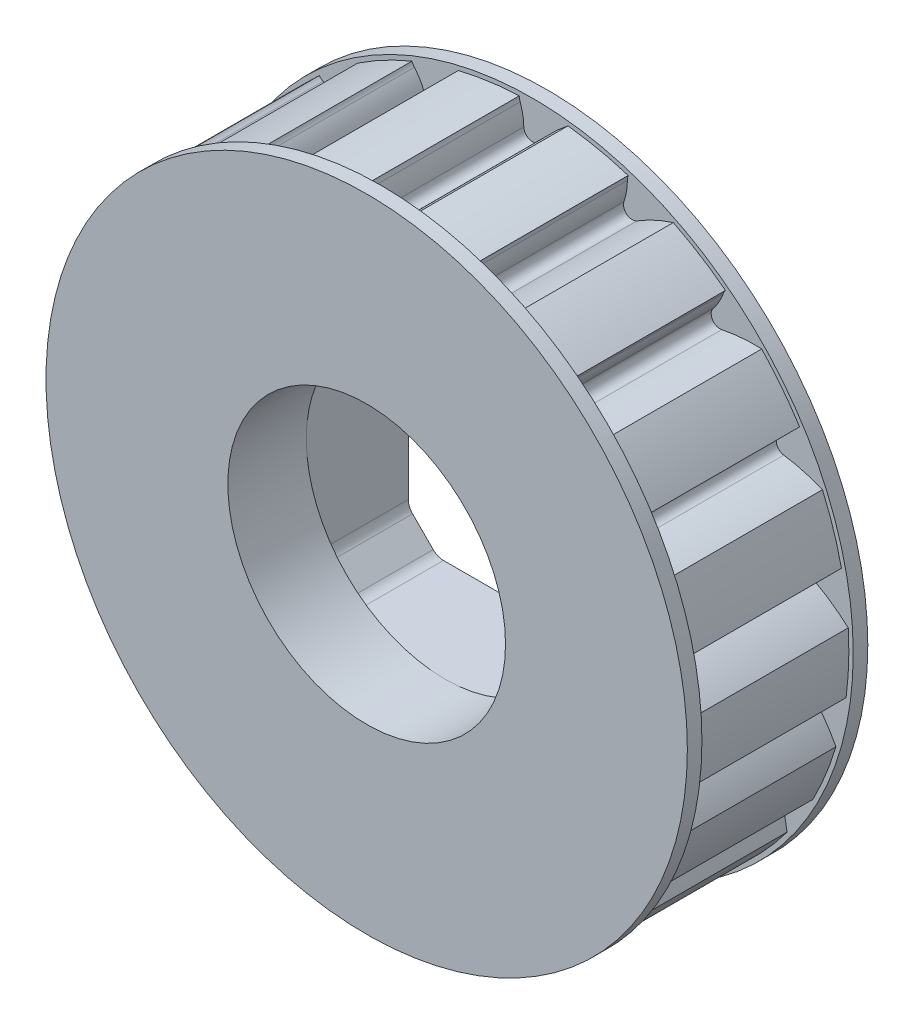
SolidWorks part; units mm, degrees
material "PA Type 6"
ref_plane "Front Plane" through (0, 0, 0) normal (0, 0, 1) x (1, 0, 0)
ref_plane "Top Plane" through (0, 0, 0) normal (0, 1, 0) x (1, 0, 0)
ref_plane "Right Plane" through (0, 0, 0) normal (1, 0, 0) x (0, 0, -1)
sketch "Sketch1" plane through (0, 0, 0) normal (0, 0, 1) x (1, 0, 0)
  line L9 (9.525, -7.1108) -> (9.525, 7.1108)
  line L10 (7.8179, -9.2321) -> (9.2321, -7.8179)
  line L11 (-7.1108, -9.525) -> (7.1108, -9.525)
  line L12 (-9.2321, -7.8179) -> (-7.8179, -9.2321)
  line L13 (-9.525, 7.1108) -> (-9.525, -7.1108)
  line L14 (-7.8179, 9.2321) -> (-9.2321, 7.8179)
  line L15 (7.1108, 9.525) -> (-7.1108, 9.525)
  line L16 (9.2321, 7.8179) -> (7.8179, 9.2321)
  line L17 (9.525, -7.1108) -> (9.525, 7.1108)
  line L18 (7.8179, -9.2321) -> (9.2321, -7.8179)
  line L19 (-7.1108, -9.525) -> (7.1108, -9.525)
  line L20 (-9.2321, -7.8179) -> (-7.8179, -9.2321)
  line L21 (-9.525, 7.1108) -> (-9.525, -7.1108)
  line L22 (-7.8179, 9.2321) -> (-9.2321, 7.8179)
  line L23 (7.1108, 9.525) -> (-7.1108, 9.525)
  line L24 (9.2321, 7.8179) -> (7.8179, 9.2321)
  circle A0 centre (0, 0) radius 25
  circle A1 centre (0, 0) radius 9.525 construction
  arc A12 (9.2321, -7.8179) -> (9.525, -7.1108) centre (8.525, -7.1108) ccw
  arc A13 (7.1108, -9.525) -> (7.8179, -9.2321) centre (7.1108, -8.525) ccw
  arc A14 (-7.8179, -9.2321) -> (-7.1108, -9.525) centre (-7.1108, -8.525) ccw
  arc A15 (-9.525, -7.1108) -> (-9.2321, -7.8179) centre (-8.525, -7.1108) ccw
  arc A16 (-9.2321, 7.8179) -> (-9.525, 7.1108) centre (-8.525, 7.1108) ccw
  arc A17 (-7.1108, 9.525) -> (-7.8179, 9.2321) centre (-7.1108, 8.525) ccw
  arc A18 (7.8179, 9.2321) -> (7.1108, 9.525) centre (7.1108, 8.525) ccw
  arc A19 (9.525, 7.1108) -> (9.2321, 7.8179) centre (8.525, 7.1108) ccw
  arc A20 (9.2321, -7.8179) -> (9.525, -7.1108) centre (8.525, -7.1108) ccw
  arc A21 (7.1108, -9.525) -> (7.8179, -9.2321) centre (7.1108, -8.525) ccw
  arc A22 (-7.8179, -9.2321) -> (-7.1108, -9.525) centre (-7.1108, -8.525) ccw
  arc A23 (-9.525, -7.1108) -> (-9.2321, -7.8179) centre (-8.525, -7.1108) ccw
  arc A24 (-9.2321, 7.8179) -> (-9.525, 7.1108) centre (-8.525, 7.1108) ccw
  arc A25 (-7.1108, 9.525) -> (-7.8179, 9.2321) centre (-7.1108, 8.525) ccw
  arc A26 (7.8179, 9.2321) -> (7.1108, 9.525) centre (7.1108, 8.525) ccw
  arc A27 (9.525, 7.1108) -> (9.2321, 7.8179) centre (8.525, 7.1108) ccw
  dimension "D2" = 50
  dimension "D1" = 19.05
  dimension "D3" = 0
extrude "Boss-Extrude1" add sketch "Sketch1" along normal up to surface (12.38 mm away)
sketch "Sketch9" plane through (0, 0, 12.38) normal (0, 0, 1) x (1, 0, 0)
  circle A0 centre (0, 0) radius 9.525
  circle A1 centre (0, 0) radius 25 construction
  circle A2 centre (0, 0) radius 25
  dimension "D1" = 19.05
extrude "Boss-Extrude4" add sketch "Sketch9" against normal up to surface (5.38 mm away)
sketch "Sketch4" plane through (0, 0, 12.38) normal (0, 0, 1) x (1, 0, 0)
  circle A3 centre (0, 0) radius 22
  circle A4 centre (0, 0) radius 22
  dimension "D1" = 3
extrude "Tread Clearance" cut sketch "Sketch4" against normal through all flip side to cut
sketch "Sketch5" plane through (0, 0, 0) normal (0, 0, 1) x (1, 0, 0)
  circle A0 centre (0, 0) radius 21.7
  circle A1 centre (0, 0) radius 22 construction
  dimension "D1" = 0.3
extrude "Cut-Extrude2" cut sketch "Sketch5" along normal offset from surface (10.38 mm away) 1 from offset 1 flip side to cut up to face at (9.525, 0, 12.38)
sketch "Sketch6" plane through (0, 0, 1) normal (0, 0, 1) x (1, 0, 0)
  line L0 (6.8404, 18.7939) -> (0, 0) construction
  line L1 (0, 0) -> (27.7968, 0) construction
  circle A0 centre (0, 0) radius 21.7 construction
  circle A1 centre (0, 0) radius 21.7 construction
  arc A2 (6.5058, 20.362) -> (6.2736, 18.9906) centre (2.3058, 20.3677) cw
  arc A3 (9.6571, 19.4327) -> (7.1571, 18.2842) centre (12.963, 8.9413) ccw
  arc A4 (6.2736, 18.9906) -> (7.1571, 18.2842) centre (6.8404, 18.7939) ccw
  circle A5 centre (0, 0) radius 20 construction
  arc A7 (6.5058, 20.362) -> (6.5598, 20.6848) centre (7.5058, 20.3606) cw
  arc A8 (6.5598, 20.6848) -> (9.6571, 19.4327) centre (0, 0) cw
  dimension "D1" = 4.2
  dimension "D2" = 11
  dimension "D3" = 1
  dimension "D4" = 0.6
  dimension "D5" = 40
  dimension "D7" = 70
  dimension "D6" = 2.5
extrude "Cut-Extrude3" cut sketch "Sketch6" along normal up to surface (10.38 mm away) up to face at (0, 22, 11.38)
pattern_circular "CirPattern4" count 18 over 360 about axis through (0, 0, 0) along (0, 0, 1) of "Cut-Extrude3"
